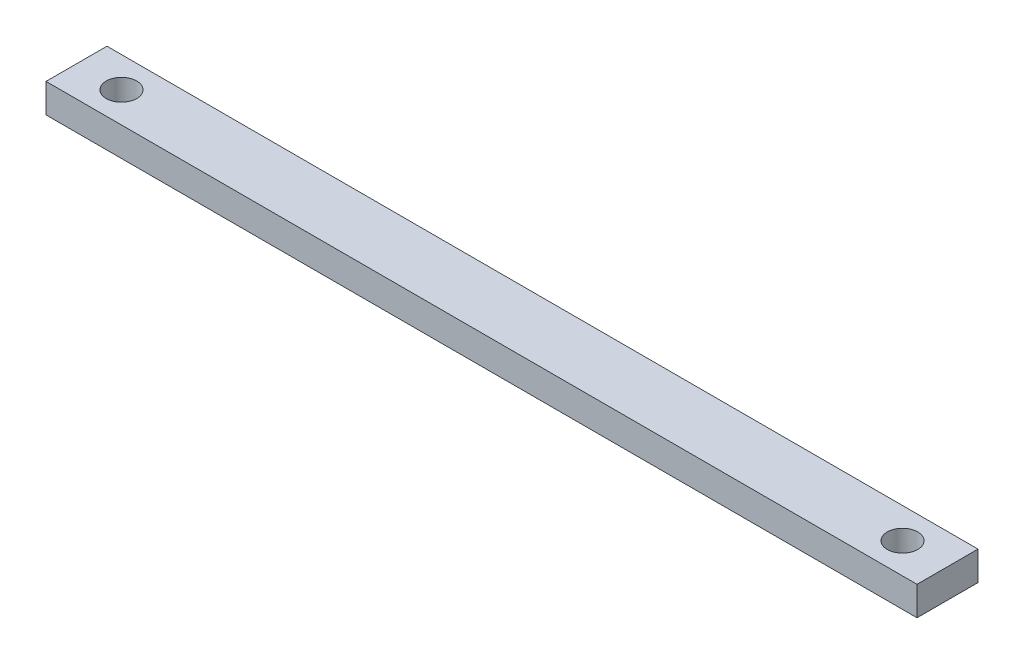
SolidWorks part; units mm, degrees
ref_plane "Plan de face" through (0, 0, 0) normal (0, 0, 1) x (1, 0, 0)
ref_plane "Plan de dessus" through (0, 0, 0) normal (0, 1, 0) x (1, 0, 0)
ref_plane "Plan de droite" through (0, 0, 0) normal (1, 0, 0) x (0, 0, -1)
sketch "Esquisse1" plane through (0, 0, 0) normal (0, 1, 0) x (1, 0, 0)
  line L1 (-300, -21) -> (300, -21)
  line L2 (-300, -21) -> (-300, 21)
  line L3 (-300, 21) -> (300, 21)
  line L4 (300, -21) -> (300, 21)
  line L5 (-300, -21) -> (300, 21) construction
  line L6 (-300, 21) -> (300, -21) construction
  point P0 (0, 0)
  dimension "D1" = 600
  dimension "D2" = 42
extrude "Boss.-Extru.1" add sketch "Esquisse1" along normal blind 20
sketch "Esquisse2" plane through (0, 20, 0) normal (0, 1, 0) x (1, 0, 0)
  line L0 (-238, 0) -> (-300, 0) construction
  line L1 (-300, -21) -> (300, -21) construction
  line L2 (-238, -21) -> (-238, 21) construction
  line L3 (300, 21) -> (-300, 21) construction
  line L4 (-238, 21) -> (-300, 21) construction
  line L5 (238, 21) -> (238, -21) construction
  line L6 (198, -21) -> (300, -21) construction
  line L7 (300, -21) -> (300, 21) construction
  line L8 (-300, 21) -> (-300, -21) construction
  line L9 (238, 0) -> (300, 0) construction
  circle A2 centre (-269, 0) radius 10.5
  circle A3 centre (269, 0) radius 10.5
  dimension "D1" = 21
  dimension "D2" = 62
  dimension "D4" = 21
  dimension "D3" = 62
extrude "Enlèv. mat.-Extru.1" cut sketch "Esquisse2" against normal blind 20
